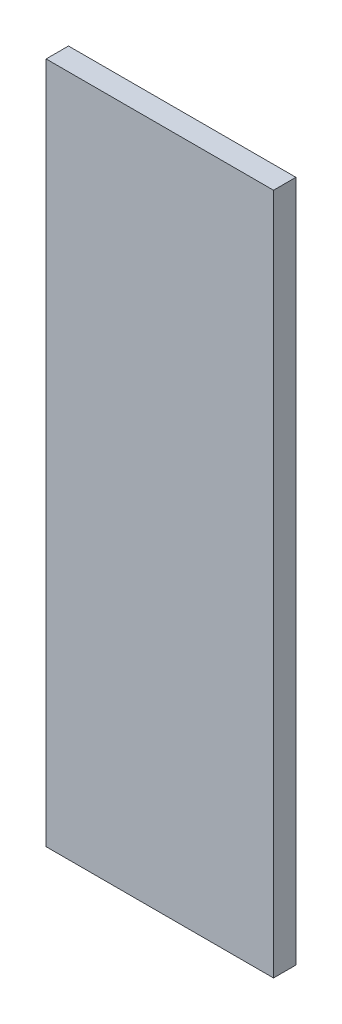
SolidWorks part; units mm, degrees
material "Ductile Iron"
ref_plane "Front Plane" through (0, 0, 0) normal (0, 0, 1) x (1, 0, 0)
ref_plane "Top Plane" through (0, 0, 0) normal (0, 1, 0) x (1, 0, 0)
ref_plane "Right Plane" through (0, 0, 0) normal (1, 0, 0) x (0, 0, -1)
sketch "Sketch2" plane through (0, 0, 0) normal (0, 0, 1) x (1, 0, 0)
  line L0 (0, 0) -> (50.8, 0) construction
  line L1 (0, -76.2) -> (50.8, -76.2)
  line L2 (0, -76.2) -> (0, 76.2)
  line L3 (0, 76.2) -> (50.8, 76.2)
  line L4 (50.8, -76.2) -> (50.8, 76.2)
  point P8 (25.4, 0)
  dimension "D1" = 152.4
  dimension "D2" = 50.8
extrude "Boss-Extrude1" add sketch "Sketch2" along normal blind 5
sketch "Sketch4" plane through (0, 0, 0) normal (0, 0, -1) x (-1, 0, 0)
  line L0 (-38.1, -69.85) -> (-38.1, 69.85) construction
  line L1 (-38.1, -69.85) -> (-12.7, -69.85) construction
  line L2 (-12.7, -69.85) -> (-12.7, 69.85) construction
  line L3 (-38.1, 69.85) -> (-12.7, 69.85) construction
  line L4 (0, 76.2) -> (0, -76.2) construction
  line L5 (0, -76.2) -> (-50.8, -76.2) construction
  line L6 (-50.8, 76.2) -> (0, 76.2) construction
  circle A0 centre (-38.1, -69.85) radius 2.4638
  circle A1 centre (-12.7, -69.85) radius 2.4638
  circle A2 centre (-12.7, 69.85) radius 2.4638
  circle A3 centre (-38.1, 69.85) radius 2.4638
  circle A5 centre (-38.1, -50.8) radius 2.4638
  circle A6 centre (-12.7, -50.8) radius 2.4638
  circle A8 centre (-38.1, -50.8) radius 4.7283 construction
  circle A9 centre (-38.1, -25.4) radius 2.4638
  circle A10 centre (-12.7, -25.4) radius 2.4638
  circle A11 centre (-38.1, 0) radius 2.4638
  circle A12 centre (-12.7, 0) radius 2.4638
  circle A13 centre (-38.1, 25.4) radius 2.4638
  circle A14 centre (-12.7, 25.4) radius 2.4638
  circle A15 centre (-38.1, 50.8) radius 2.4638
  circle A16 centre (-12.7, 50.8) radius 2.4638
  dimension "D1" = 4.9276
  dimension "D7" = 25.4
  dimension "D2" = 25.4
  dimension "D3" = 12.7
  dimension "D4" = 6.35
  dimension "D5" = 6.35
  dimension "D6" = 5
extrude "Cut-Extrude1" [suppressed] cut sketch "Sketch4" against normal through all both and the other way through all
